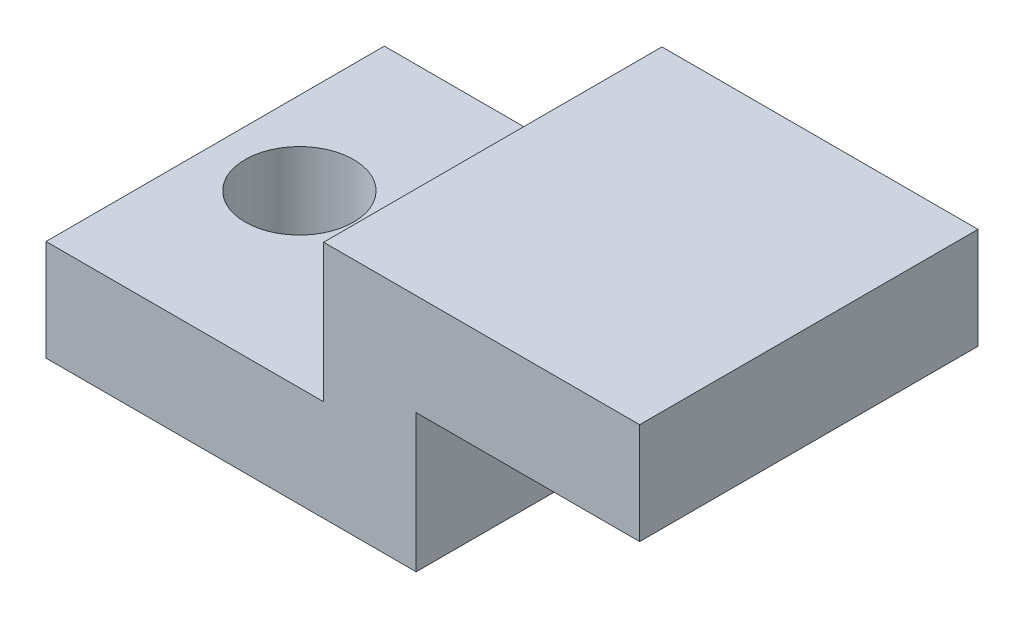
SolidWorks part; units mm, degrees
ref_plane "Front Plane" through (0, 0, 0) normal (0, 0, 1) x (1, 0, 0)
ref_plane "Top Plane" through (0, 0, 0) normal (0, 1, 0) x (1, 0, 0)
ref_plane "Right Plane" through (0, 0, 0) normal (1, 0, 0) x (0, 0, -1)
sketch "Sketch1" plane through (0, 0, 0) normal (0, 0, 1) x (1, 0, 0)
  line L0 (-32.5136, -17.418) -> (22.1918, -17.418)
  line L1 (22.1918, -17.418) -> (22.1918, 2.9675)
  line L2 (22.1918, 2.9675) -> (55.2214, 2.9675)
  line L3 (55.2214, 2.9675) -> (55.2214, 17.9341)
  line L4 (55.2214, 17.9341) -> (8.5155, 17.9341)
  line L5 (8.5155, 17.9341) -> (8.5155, -2.4848)
  line L6 (8.5155, -2.4848) -> (-32.5136, -2.4848)
  line L7 (-32.5136, -2.4848) -> (-32.5136, -17.418)
extrude "Boss-Extrude1" add sketch "Sketch1" along normal blind 50
sketch "Sketch2" plane through (0, -2.4848, 0) normal (0, 1, 0) x (1, 0, 0)
  circle A0 centre (-20.2717, -24.7924) radius 8.0159
extrude "Cut-Extrude1" cut sketch "Sketch2" against normal blind 50
